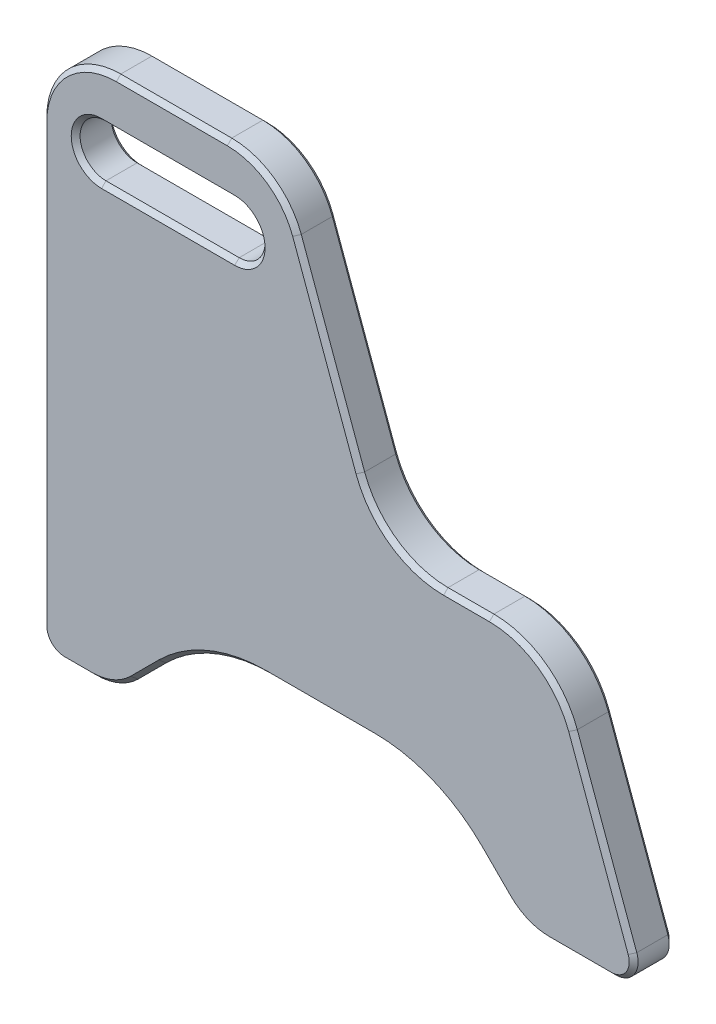
SolidWorks part; units mm, degrees
ref_plane "Plan de face" through (0, 0, 0) normal (0, 0, 1) x (1, 0, 0)
ref_plane "Plan de dessus" through (0, 0, 0) normal (0, 1, 0) x (1, 0, 0)
ref_plane "Plan de droite" through (0, 0, 0) normal (1, 0, 0) x (0, 0, -1)
sketch "Esquisse1" plane through (0, 0, 0) normal (0, 0, 1) x (1, 0, 0)
  line L0 (0, 0) -> (0, 360)
  line L1 (0, 360) -> (160, 360)
  line L3 (406.0293, 0) -> (0, 0)
  line L4 (406.0293, 0) -> (344.1543, 170)
  line L5 (344.1543, 170) -> (229.1543, 170)
  line L6 (229.1543, 170) -> (160, 360)
  dimension "D1" = 360
  dimension "D2" = 160
  dimension "D3" = 70
  dimension "D4" = 115
  dimension "D5" = 170
extrude "Boss.-Extru.1" add sketch "Esquisse1" along normal blind 27
sketch "Esquisse2" plane through (0, 0, 27) normal (0, 0, 1) x (1, 0, 0)
  line L0 (50, 0) -> (110, 60)
  line L1 (0, 0) -> (406.0293, 0) construction
  line L2 (110, 60) -> (266.0293, 60)
  line L3 (266.0293, 60) -> (326.0293, 0)
  line L4 (326.0293, 0) -> (50, 0)
  dimension "D1" = 45
  dimension "D2" = 45
  dimension "D3" = 50
  dimension "D4" = 80
  dimension "60" = 60
extrude "Enlèv. mat.-Extru.1" cut sketch "Esquisse2" against normal through all both and the other way through all
fillet "Congé3" radius 60 2 edges at (344.1543, 170, 13.5) (229.1543, 170, 13.5)
fillet "Congé4" radius 50 2 edges at (0, 360, 13.5) (160, 360, 13.5)
fillet "Congé5" radius 100 2 edges at (266.0293, 60, 13.5) (110, 60, 13.5)
fillet "Congé6" radius 15 2 edges at (0, 0, 13.5) (406.0293, 0, 13.5)
fillet "Congé7" radius 40 2 edges at (326.0293, 0, 13.5) (50, 0, 13.5)
sketch "Esquisse3" plane through (0, 0, 27) normal (0, 0, 1) x (1, 0, 0)
  line L0 (40, 310) -> (130, 310) construction
  line L1 (40, 327.5) -> (130, 327.5)
  line L2 (40, 292.5) -> (130, 292.5)
  line L3 (124.9896, 360) -> (50, 360) construction
  line L9 (0, 310) -> (0, 15) construction
  arc A0 (40, 327.5) -> (40, 292.5) centre (40, 310) ccw
  arc A1 (130, 292.5) -> (130, 327.5) centre (130, 310) ccw
  point P2 (85, 310)
  dimension "D1" = 35
  dimension "D2" = 90
  dimension "D3" = 50
  dimension "D4" = 85
extrude "Enlèv. mat.-Extru.2" cut sketch "Esquisse3" against normal through all both and the other way through all
chamfer "Chanfrein1" distance 3 angle 45 48 edges at (396.8943, 6.3964, 0) (378.613, 75.3258, 0) (336.5565, 159.1491, 0) (286.6543, 170, 0) (236.7522, 180.8509, 0) (193.3797, 268.2899, 0) (153.6684, 350.9576, 0) (87.4948, 360, 0) (14.6447, 345.3553, 0) (0, 162.5, 0) (4.3934, 4.3934, 0) (24.2157, 0, 0) (48.7388, 3.0448, 0) (71.2132, 21.2132, 0) (113.153, 52.388, 0) (188.0146, 60, 0) (262.8763, 52.388, 0) (304.8161, 21.2132, 0) (327.2905, 3.0448, 0) (363.6024, 0, 0) (85, 327.5, 0) (147.5, 310, 0) (85, 292.5, 0) (22.5, 310, 0) (262.8763, 52.388, 27) (188.0146, 60, 27) (113.153, 52.388, 27) (71.2132, 21.2132, 27) (48.7388, 3.0448, 27) (24.2157, 0, 27) (4.3934, 4.3934, 27) (0, 162.5, 27) (14.6447, 345.3553, 27) (87.4948, 360, 27) (153.6684, 350.9576, 27) (193.3797, 268.2899, 27) (236.7522, 180.8509, 27) (286.6543, 170, 27) (336.5565, 159.1491, 27) (378.613, 75.3258, 27) (396.8943, 6.3964, 27) (363.6024, 0, 27) (327.2905, 3.0448, 27) (304.8161, 21.2132, 27) (147.5, 310, 27) (85, 327.5, 27) (22.5, 310, 27) (85, 292.5, 27)
